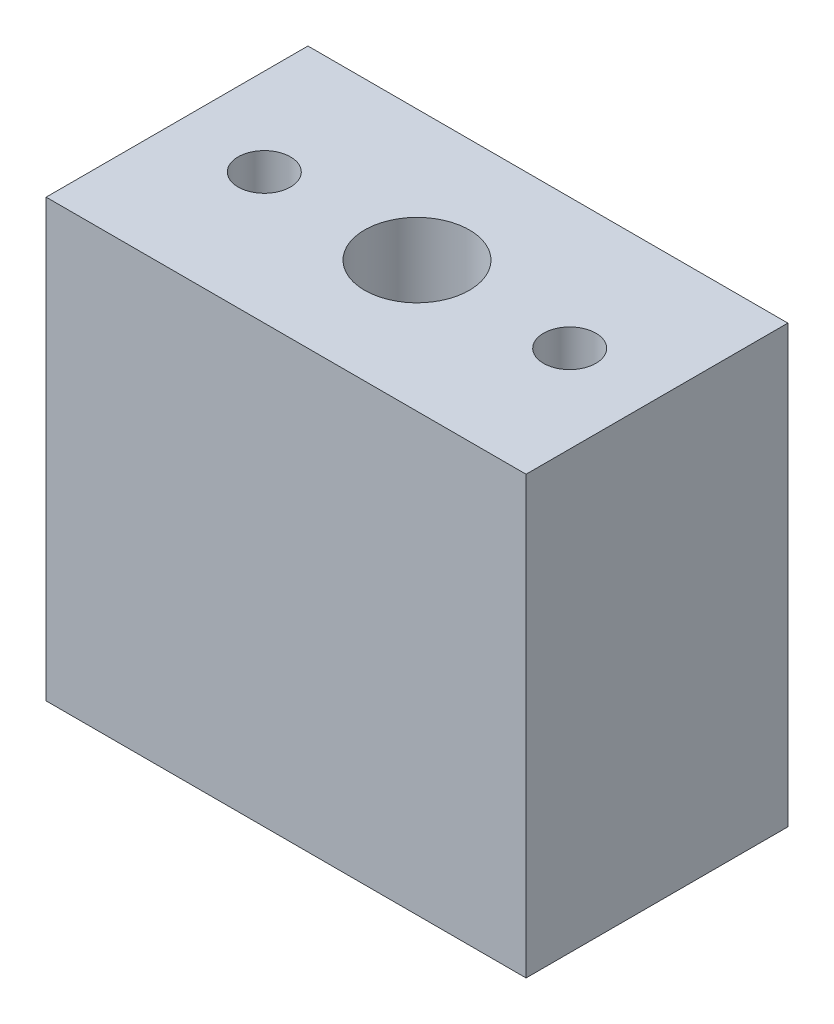
SolidWorks part; units mm, degrees
ref_plane "Front Plane" through (0, 0, 0) normal (0, 0, 1) x (1, 0, 0)
ref_plane "Top Plane" through (0, 0, 0) normal (0, 1, 0) x (1, 0, 0)
ref_plane "Right Plane" through (0, 0, 0) normal (1, 0, 0) x (0, 0, -1)
sketch "Sketch1" plane through (0, 0, 0) normal (0, 1, 0) x (1, 0, 0)
  line L3 (1.5, 1.5) -> (-4, 1.5)
  line L6 (1.5, 1.5) -> (1.5, -1.5)
  line L7 (1.5, -1.5) -> (-4, -1.5)
  line L8 (-4, 1.5) -> (-4, -1.5)
  line L9 (1.5, 1.5) -> (-4, -1.5) construction
  line L10 (1.5, -1.5) -> (-4, 1.5) construction
  circle A1 centre (-1.25, 0) radius 0.6
  circle A8 centre (-3, 0) radius 0.3
  circle A9 centre (0.5, 0) radius 0.3
  point P12 (-3, 0)
  point P20 (0.5, 0)
  dimension "D1" = 3
  dimension "D2" = 5.5
extrude "Boss-Extrude1" add sketch "Sketch1" along normal blind 5
